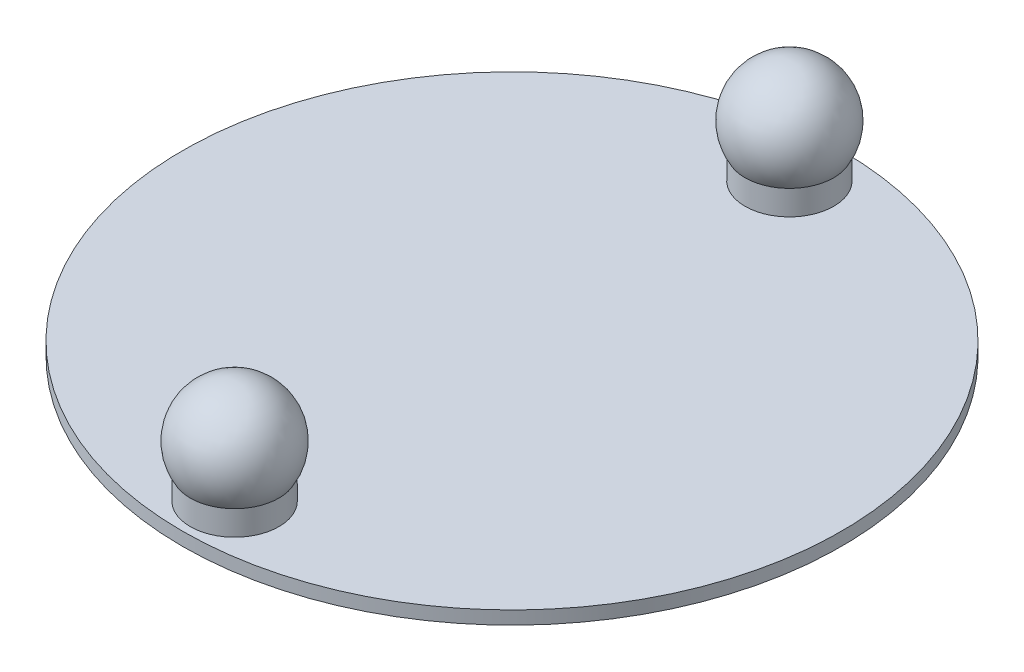
SolidWorks part; units mm, degrees
material "A-Glass Fiber"
ref_plane "Front Plane" through (0, 0, 0) normal (0, 0, 1) x (1, 0, 0)
ref_plane "Top Plane" through (0, 0, 0) normal (0, 1, 0) x (1, 0, 0)
ref_plane "Right Plane" through (0, 0, 0) normal (1, 0, 0) x (0, 0, -1)
sketch "Sketch1" plane through (0, 0, 0) normal (0, 1, 0) x (1, 0, 0)
  circle A0 centre (0, 0) radius 20
  dimension "D1" = 40
extrude "PCB" add sketch "Sketch1" along normal blind 0.8
sketch "Sketch2" plane through (0, 0.8, 0) normal (0, 1, 0) x (1, 0, 0)
  line L0 (0, 20) -> (0, 0) construction
  line L1 (-9, 16) -> (9, 16)
  line L2 (-9, 16) -> (-9, 12)
  line L3 (-9, 12) -> (9, 12)
  line L4 (9, 16) -> (9, 12)
  circle A0 centre (0, 0) radius 20 construction
  point P9 (0, 16)
  dimension "D1" = 4
  dimension "D2" = 18
  dimension "D3" = 16
sketch "Sketch3" plane through (0, 0, 0) normal (1, 0, 0) x (0, 0, -1)
  line L0 (-16.835, 7.13) -> (-16.835, 0.8)
  line L4 (-16.835, 0.8) -> (-19.5267, 0.8)
  line L5 (-19.5267, 2.3) -> (-19.5267, 0.8)
  arc A0 (-19.5267, 2.3) -> (-16.835, 7.13) centre (-16.835, 3.965) cw
  dimension "D4" = 3.165
  dimension "D3" = 3.165
  dimension "D1" = 6.33
  dimension "D2" = 1.5
revolve "Revolve1" add sketch "Sketch3" angle 360 about L0
mirror "Mirror1" about plane through (0, 0, 0) normal (0, 0, 1) of "Revolve1"
sketch "Sketch4" plane through (0, 0.8, 0) normal (0, 1, 0) x (1, 0, 0)
  line L0 (0, -16.835) -> (0, 16.835) construction
